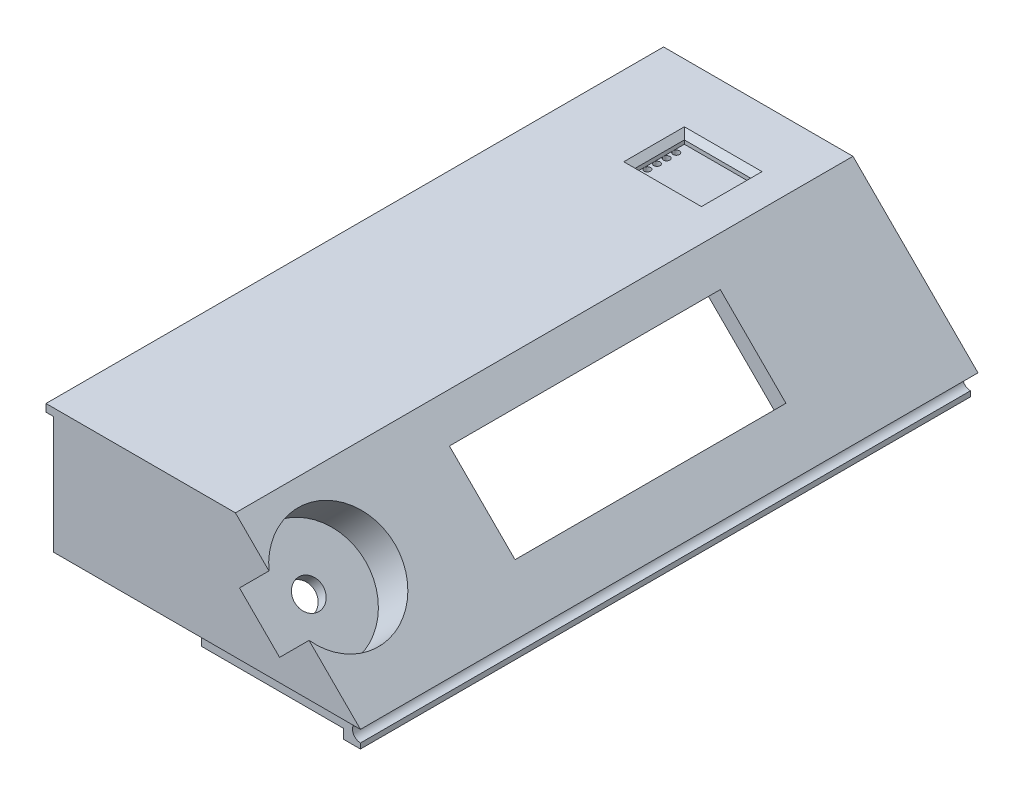
SolidWorks part; units mm, degrees
ref_plane "Спереди" through (0, 0, 0) normal (0, 0, 1) x (1, 0, 0)
ref_plane "Сверху" through (0, 0, 0) normal (0, 1, 0) x (1, 0, 0)
ref_plane "Справа" through (0, 0, 0) normal (1, 0, 0) x (0, 0, -1)
sketch "Эскиз1" plane through (0, 0, 0) normal (0, 0, 1) x (1, 0, 0)
  line L0 (0, 0) -> (-31, 31)
  line L1 (0, 0) -> (2, 0)
  line L2 (2, 0) -> (-31, 33)
  line L3 (-31, 33) -> (-81, 33)
  line L7 (-81, 31) -> (-31, 31)
  line L8 (-81, 33) -> (-81, 31)
  dimension "D1" = 31
  dimension "D2" = 45
  dimension "D3" = 2
  dimension "D4" = 2
  dimension "D5" = 83
extrude "Бобышка-Вытянуть1" add sketch "Эскиз1" along normal blind 163
sketch "Эскиз2" plane through (0, 0, 163) normal (0, 0, 1) x (1, 0, 0)
  line L0 (2, 0) -> (-31, 33)
  line L1 (-31, 33) -> (-79, 33)
  line L2 (-31, 33) -> (-81, 33) construction
  line L3 (-81, 33) -> (-81, 31) construction
  line L4 (-79, 33) -> (-79, 0)
  line L5 (-79, 0) -> (2, 0)
  dimension "D1" = 2
extrude "Бобышка-Вытянуть2" add sketch "Эскиз2" against normal blind 2
sketch "Эскиз3" plane through (0, 0, 0) normal (0, 0, -1) x (-1, 0, 0)
  line L0 (0, 0) -> (31, 31)
  line L1 (31, 31) -> (79, 31)
  line L2 (79, 31) -> (79, 28)
  line L3 (79, 31) -> (79, 0) construction
  line L4 (79, 28) -> (32.2426, 28)
  line L5 (32.2426, 28) -> (4.2426, 0)
  line L6 (79, 0) -> (0, 0) construction
  line L7 (0, 0) -> (4.2426, 0)
  dimension "D1" = 3
  dimension "D2" = 3
extrude "Бобышка-Вытянуть3" add sketch "Эскиз3" against normal blind 2
sketch "Эскиз4" plane through (0, 0, 0) normal (0, -1, 0) x (1, 0, 0)
  line L1 (-79, 161) -> (-42, 161)
  line L2 (-79, 161) -> (-79, 151)
  line L3 (-79, 151) -> (-42, 151)
  line L4 (-42, 161) -> (-42, 151)
  dimension "D1" = 10
  dimension "D2" = 37
extrude "Бобышка-Вытянуть4" add sketch "Эскиз4" against normal blind 2
sketch "Эскиз5" plane through (1, 1, 0) normal (0.7071, 0.7071, 0) x (0, 0, -1)
  line L0 (-161, 23.8406) -> (-2, 23.8406) construction
  line L3 (-161, 0) -> (-161, 43.8406) construction
  line L4 (-2, 43.8406) -> (-2, 0) construction
  line L5 (-163, -1.4142) -> (-163, 45.2548) construction
  line L6 (-41.5, 36.0906) -> (-113, 36.0906)
  line L7 (-41.5, 36.0906) -> (-41.5, 11.5906)
  line L8 (-41.5, 11.5906) -> (-113, 11.5906)
  line L9 (-113, 36.0906) -> (-113, 11.5906)
  point P11 (-113, 23.8406)
  dimension "D1" = 20
  dimension "D2" = 71.5
  dimension "D3" = 24.5
  dimension "D4" = 50
extrude "Вырез-Вытянуть1" cut sketch "Эскиз5" against normal through all
sketch "Эскиз6" plane through (0, 0, 0) normal (-0.7071, -0.7071, 0) x (0, 0, 1)
  line L0 (113, 36.0906) -> (113, 11.5906) construction
  line L1 (113, 11.5906) -> (41.5, 11.5906) construction
  line L2 (41.5, 11.5906) -> (41.5, 36.0906) construction
  line L3 (41.5, 36.0906) -> (113, 36.0906) construction
  line L4 (113, 36.0906) -> (113, 11.5906)
  line L5 (113, 11.5906) -> (41.5, 11.5906)
  line L6 (41.5, 11.5906) -> (41.5, 36.0906)
  line L7 (41.5, 36.0906) -> (113, 36.0906)
  line L9 (117, 40.0906) -> (37.5, 40.0906)
  line L10 (117, 40.0906) -> (117, 7.5906)
  line L11 (117, 7.5906) -> (37.5, 7.5906)
  line L12 (37.5, 40.0906) -> (37.5, 7.5906)
  dimension "D1" = 4
  dimension "D2" = 4
  dimension "D3" = 4
  dimension "D4" = 4
extrude "Бобышка-Вытянуть5" add sketch "Эскиз6" along normal blind 3
sketch "Эскиз8" plane through (0, 0, 37.5) normal (0, 0, -1) x (-1, 0, 0)
  line L0 (28.3483, 28.3483) -> (30.4697, 26.227)
  line L1 (30.4697, 26.227) -> (35.2426, 31)
  line L2 (79, 31) -> (31, 31) construction
  line L3 (35.2426, 31) -> (31, 31)
  line L4 (31, 31) -> (28.3483, 28.3483)
extrude "Бобышка-Вытянуть6" add sketch "Эскиз8" against normal up to surface (79.5 mm away) up to face at (-17.9185, 15.7972, 117)
sketch "Эскиз10" plane through (1, 1, 0) normal (0.7071, 0.7071, 0) x (0, 0, -1)
  line L0 (-113, 23.8406) -> (-163, 23.8406) construction
  line L1 (-113, 36.0906) -> (-113, 11.5906) construction
  line L2 (-163, -1.4142) -> (-163, 45.2548) construction
  line L4 (-163, 45.2548) -> (0, 45.2548) construction
  circle A0 centre (-150, 25.2548) radius 15
  dimension "D1" = 30
  dimension "D2" = 13
  dimension "D3" = 20
extrude "Вырез-Вытянуть2" cut sketch "Эскиз10" against normal blind 14
sketch "Эскиз11" plane through (1, 1, 0) normal (0.7071, 0.7071, 0) x (0, 0, -1)
  line L0 (-163, -1.4142) -> (-163, 17.7715) construction
  line L1 (-163, 32.7381) -> (-163, 45.2548) construction
  line L2 (-163, 32.7381) -> (-163, 35.7381)
  line L3 (-163, 17.7715) -> (-163, 14.7715)
  arc A0 (-163, 32.7381) -> (-163, 17.7715) centre (-150, 25.2548) cw
  arc A1 (-163, 35.7381) -> (-163, 14.7715) centre (-150, 25.2548) cw
  dimension "D1" = 3
extrude "Бобышка-Вытянуть8" add sketch "Эскиз11" against normal up to surface (14 mm away) up to face at (-26.7574, 8.9584, 162.0383)
sketch "Эскиз12" plane through (-8.8995, -8.8995, 0) normal (0.7071, 0.7071, 0) x (0, 0, -1)
  line L0 (-163, 32.7381) -> (-163, 45.2548) construction
  line L1 (-163, -1.4142) -> (-163, 17.7715) construction
  line L2 (-163, 35.7377) -> (-163, 14.772)
  arc A0 (-163, 35.7377) -> (-163, 14.772) centre (-150, 25.2548) cw
  circle A1 centre (-150, 25.2548) radius 3.75
  dimension "D1" = 16.7
  dimension "D2" = 7.5
extrude "Бобышка-Вытянуть9" add sketch "Эскиз12" along normal blind 3
sketch "Эскиз14" plane through (0, 31, 0) normal (0, -1, 0) x (1, 0, 0)
  line L0 (-79, 2) -> (-31, 2) construction
  line L1 (-41, 17) -> (-58.5, 17)
  line L2 (-41, 17) -> (-41, 30)
  line L3 (-41, 30) -> (-58.5, 30)
  line L4 (-58.5, 17) -> (-58.5, 30)
  dimension "D1" = 13
  dimension "D2" = 17.5
  dimension "D3" = 15
  dimension "D4" = 10
extrude "Вырез-Вытянуть3" cut sketch "Эскиз14" against normal through all both and the other way through all
sketch "Эскиз15" plane through (0, 31, 0) normal (0, -1, 0) x (1, 0, 0)
  line L0 (-58.5, 17) -> (-58.5, 30) construction
  line L1 (-41, 17) -> (-58.5, 17) construction
  line L2 (-58.5, 30) -> (-41, 30) construction
  line L3 (-41, 30) -> (-41, 17) construction
  line L4 (-58.5, 17) -> (-58.5, 30)
  line L5 (-41, 17) -> (-58.5, 17)
  line L6 (-58.5, 30) -> (-41, 30)
  line L7 (-41, 30) -> (-41, 17)
  line L9 (-38, 33) -> (-61.5, 33)
  line L10 (-38, 33) -> (-38, 14)
  line L11 (-38, 14) -> (-61.5, 14)
  line L12 (-61.5, 33) -> (-61.5, 14)
  dimension "D1" = 3
  dimension "D2" = 3
  dimension "D3" = 3
  dimension "D4" = 3
extrude "Бобышка-Вытянуть10" add sketch "Эскиз15" along normal blind 0.5
sketch "Эскиз16" plane through (0, 30.5, 0) normal (0, -1, 0) x (1, 0, 0)
  line L1 (-38, 33) -> (-61.5, 33)
  line L2 (-38, 33) -> (-38, 14)
  line L3 (-38, 14) -> (-61.5, 14)
  line L4 (-61.5, 33) -> (-61.5, 14)
extrude "Бобышка-Вытянуть11" add sketch "Эскиз16" along normal blind 2
chamfer "Фаска2" distance 2 angle 45 4 edges at (-49.75, 31, 14) (-61.5, 31, 23.5) (-38, 31, 23.5) (-49.75, 31, 33)
chamfer "Фаска3" distance 1.5 angle 45 4 edges at (-58.5, 33, 23.5) (-49.75, 33, 17) (-49.75, 33, 30) (-41, 33, 23.5)
sketch "Эскиз17" plane through (0, 30.5, 0) normal (0, 1, 0) x (1, 0, 0)
  line L0 (-61.5, -14) -> (-38, -14) construction
  line L3 (-58.5, -17) -> (-58.5, -30) construction
  circle A1 centre (-57.65, -20) radius 0.85
  circle A2 centre (-57.65, -22.54) radius 0.85
  circle A3 centre (-57.65, -25.08) radius 0.85
  circle A4 centre (-57.65, -27.62) radius 0.85
  dimension "D1" = 1.7
  dimension "D2" = 0.85
  dimension "D3" = 4
  dimension "D4" = 2.54
  dimension "D5" = 2.54
  dimension "D6" = 2.54
  dimension "D7" = 6
extrude "Вырез-Вытянуть4" cut sketch "Эскиз17" against normal blind 10
sketch "Эскиз18" plane through (0, 0, 161) normal (0, 0, -1) x (-1, 0, 0)
  line L1 (79, 31) -> (74, 31)
  line L2 (79, 31) -> (79, 24)
  line L3 (79, 24) -> (74, 24)
  line L4 (74, 31) -> (74, 24)
  dimension "D1" = 7
  dimension "D2" = 5
extrude "Бобышка-Вытянуть12" add sketch "Эскиз18" along normal up to surface (161 mm away)
sketch "Эскиз19" plane through (0, 0, 0) normal (0, 0, -1) x (-1, 0, 0)
  line L0 (79, 24) -> (79, 31) construction
  line L1 (81, 31) -> (79, 31) construction
  circle A0 centre (79, 28) radius 2.1
  dimension "D1" = 4.2
  dimension "D2" = 3
extrude "Вырез-Вытянуть5" cut sketch "Эскиз19" against normal up to surface (161 mm away) up to face at (-42.5192, 13.9694, 161)
sketch "Эскиз20" plane through (0, 24, 0) normal (0, -1, 0) x (1, 0, 0)
  line L0 (-74, 0) -> (-74, 161) construction
  line L1 (-79, 161) -> (-74, 161)
  line L2 (-79, 161) -> (-79, 153)
  line L3 (-79, 153) -> (-74, 153)
  line L4 (-74, 161) -> (-74, 153)
  dimension "D1" = 8
extrude "Бобышка-Вытянуть13" add sketch "Эскиз20" along normal up to surface (22 mm away) up to face at (-60.5, 2, 156)
sketch "Эскиз21" plane through (0, 0, 0) normal (0, -1, 0) x (1, 0, 0)
  line L0 (-79, 0) -> (-79, 163) construction
  line L2 (-79, 163) -> (2, 163) construction
  circle A0 centre (-79, 159) radius 2.1
  dimension "D1" = 4.2
  dimension "D2" = 4
extrude "Вырез-Вытянуть6" cut sketch "Эскиз21" against normal up to vertex (30.1 mm away)
sketch "Эскиз22" plane through (0, 0, 161) normal (0, 0, -1) x (-1, 0, 0)
  line L0 (4.5, -1.5) -> (4.5, 4.5)
  line L2 (0, 0) -> (0, -6.5)
  line L3 (0, -6.5) -> (4.5, -6.5)
  line L4 (4.5, -1.5) -> (4.5, -6.5)
  line L5 (31, 31) -> (0, 0) construction
  line L6 (4.5, 4.5) -> (0, 0)
  dimension "D1" = 6.5
  dimension "D2" = 4.5
extrude "Бобышка-Вытянуть14" add sketch "Эскиз22" along normal up to surface (161 mm away)
sketch "Эскиз23" plane through (0, 0, 0) normal (0, 0, -1) x (-1, 0, 0)
  line L0 (0, 0) -> (0, -6.5) construction
  line L1 (0, 0) -> (-2, 0) construction
  circle A0 centre (0, -3) radius 2.1
  dimension "D1" = 4.2
  dimension "D2" = 3
extrude "Вырез-Вытянуть7" cut sketch "Эскиз23" against normal through all both and the other way through all
sketch "Эскиз24" plane through (0, 0, 0) normal (0, 0, -1) x (-1, 0, 0)
  line L0 (74, 24) -> (74, 28)
  line L1 (74, 28) -> (32.2426, 28)
  line L2 (32.2426, 28) -> (4.5, 0.2574)
  line L3 (74, 24) -> (32.2426, 24)
  line L4 (32.2426, 24) -> (4.5, -3.7426)
  line L5 (4.5, -6.5) -> (4.5, 0.2574) construction
  line L6 (4.5, -3.7426) -> (4.5, 0.2574)
extrude "Бобышка-Вытянуть15" add sketch "Эскиз24" against normal up to surface (2 mm away) up to face at (-36.7071, 20.4596, 2)
sketch "Эскиз25" plane through (0, 2, 0) normal (0, 1, 0) x (1, 0, 0)
  line L0 (-42, -151) -> (-79, -151)
  line L1 (-42, -151) -> (-42, -161)
  line L2 (-42, -161) -> (-4.5, -161)
  line L3 (-4.5, -161) -> (-4.5, -159)
  line L4 (-79, -151) -> (-79, -156.9) construction
  line L5 (-4.5, -159) -> (-40, -159)
  line L6 (-40, -159) -> (-40, -149)
  line L7 (-79, -151) -> (-42, -151) construction
  line L9 (-79, -151) -> (-79, -149)
  line L10 (-79, -149) -> (-40, -149)
  line L11 (-4.5, -2) -> (-4.5, -161) construction
  dimension "D1" = 2
  dimension "D2" = 2
  dimension "D3" = 2
extrude "Бобышка-Вытянуть16" add sketch "Эскиз25" against normal blind 6
fillet "Скругление1" radius 6 1 edges at (-40, -1, 149)
chamfer "Фаска5" distance 3 angle 60 1 edges at (-46.8995, 2, 161)
